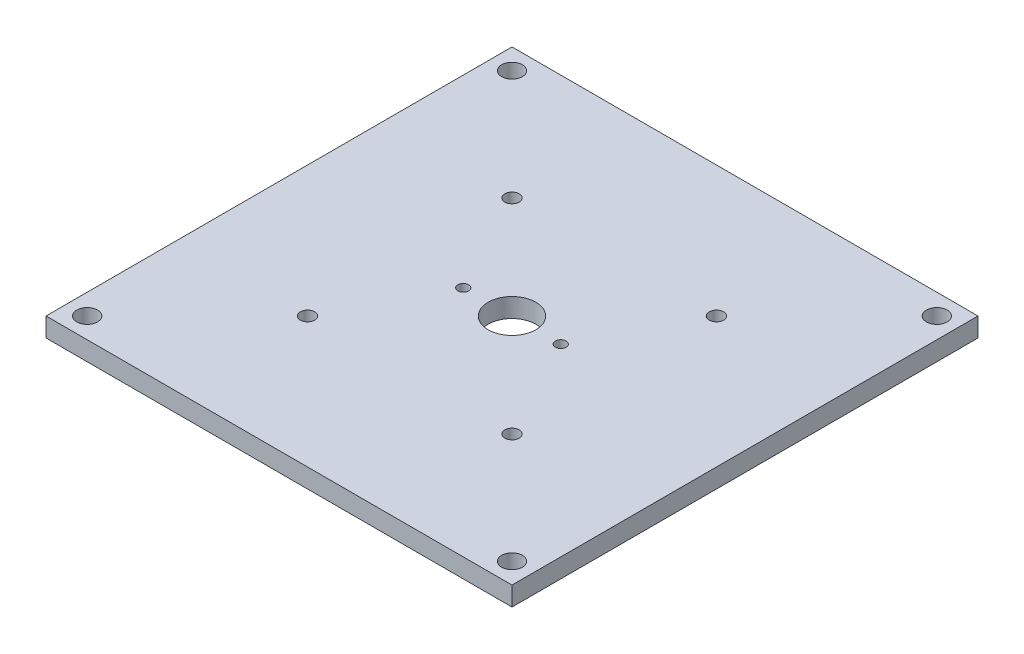
SolidWorks part; units mm, degrees
material "Pin"
ref_plane "Plan de face" through (0, 0, 0) normal (0, 0, 1) x (1, 0, 0)
ref_plane "Plan de dessus" through (0, 0, 0) normal (0, 1, 0) x (1, 0, 0)
ref_plane "Plan de droite" through (0, 0, 0) normal (1, 0, 0) x (0, 0, -1)
sketch "Esquisse1" plane through (0, 0, 0) normal (0, 1, 0) x (1, 0, 0)
  line L1 (-77.5, 77.5) -> (77.5, 77.5)
  line L2 (-77.5, 77.5) -> (-77.5, -77.5)
  line L3 (-77.5, -77.5) -> (77.5, -77.5)
  line L4 (77.5, 77.5) -> (77.5, -77.5)
  point P5 (0, 77.5)
  point P6 (-77.5, 0)
  dimension "D1" = 155
  dimension "D2" = 155
extrude "Boss.-Extru.1" add sketch "Esquisse1" along normal blind 6.35
sketch "Esquisse3" plane through (0, 6.35, 0) normal (0, 1, 0) x (1, 0, 0)
  line L1 (-70.65, 70.65) -> (70.65, 70.65) construction
  line L2 (-70.65, 70.65) -> (-70.65, -70.65) construction
  line L3 (-70.65, -70.65) -> (70.65, -70.65) construction
  line L4 (70.65, 70.65) -> (70.65, -70.65) construction
  circle A0 centre (-70.65, 70.65) radius 3.4417
  circle A1 centre (70.65, 70.65) radius 3.4417
  circle A2 centre (70.65, -70.65) radius 3.4417
  circle A3 centre (-70.65, -70.65) radius 3.4417
  point P5 (0, 70.65)
  point P7 (70.65, 0)
  dimension "D3" = 6.8834
  dimension "D1" = 141.3
  dimension "D2" = 141.3
extrude "lazy_susan_bolt_pattern" cut sketch "Esquisse3" against normal up to surface (6.35 mm away) up to face at (0, 0, 0)
sketch "Esquisse4" plane through (0, 6.35, 0) normal (0, 1, 0) x (1, 0, 0)
  circle A0 centre (0, 0) radius 7.9375
  dimension "D1" = 15.875
extrude "Enlèv. mat.-Extru.2" cut sketch "Esquisse4" against normal up to surface (6.35 mm away) up to face at (-70.65, 0, -67.2083)
sketch "Esquisse5" plane through (0, 6.35, 0) normal (0, 1, 0) x (1, 0, 0)
  line L1 (-34, 34) -> (34, 34) construction
  line L2 (-34, 34) -> (-34, -34) construction
  line L3 (-34, -34) -> (34, -34) construction
  line L4 (34, 34) -> (34, -34) construction
  point P6 (0, 34)
  point P8 (34, 0)
  dimension "D1" = 68
  dimension "D2" = 68
hole_wizard "Dégagement M41" positions "Esquisse6" profile "Esquisse7" hole size "M4" standard "Ansi Metric" end condition through all
sketch "Esquisse6" plane through (0, 6.35, 0) normal (0, 1, 0) x (1, 0, 0)
  point P0 (-34, 34)
  point P3 (34, 34)
  point P6 (34, -34)
  point P9 (-34, -34)
sketch "Esquisse7" plane through (-34, 6.35, -34) normal (1, 0, 0) x (0, 0, 1)
  line L0 (0, 0) -> (0, 6.35)
  line L1 (0, 6.35) -> (2.4, 6.35)
  line L2 (2.4, 6.35) -> (2.4, 0)
  line L5 (2.4, 0) -> (0, 0)
  line L11 (0, -6.35) -> (0, 107.95) construction
  dimension "Diamètre du perçage jusqu'au prochain" = 4.8
  dimension "Profondeur du perçage jusqu'au prochain" = 6.35
sketch "Esquisse9" plane through (0, 6.35, 0) normal (0, 1, 0) x (1, 0, 0)
  line L0 (-16.215, 0) -> (16.215, 0) construction
  point P4 (0, 0)
  dimension "D1" = 32.43
hole_wizard "Dégagement M31" positions "Esquisse10" profile "Esquisse11" hole size "M3" standard "Ansi Metric" end condition through all
sketch "Esquisse10" plane through (0, 6.35, 0) normal (0, 1, 0) x (1, 0, 0)
  point P0 (16.215, 0)
  point P3 (-16.215, 0)
sketch "Esquisse11" plane through (16.215, 6.35, 0) normal (1, 0, 0) x (0, 0, 1)
  line L0 (0, 0) -> (0, 6.35)
  line L1 (0, 6.35) -> (1.8, 6.35)
  line L2 (1.8, 6.35) -> (1.8, 0)
  line L5 (1.8, 0) -> (0, 0)
  line L11 (0, -6.35) -> (0, 107.95) construction
  dimension "Diamètre du perçage jusqu'au prochain" = 3.6
  dimension "Profondeur du perçage jusqu'au prochain" = 6.35
